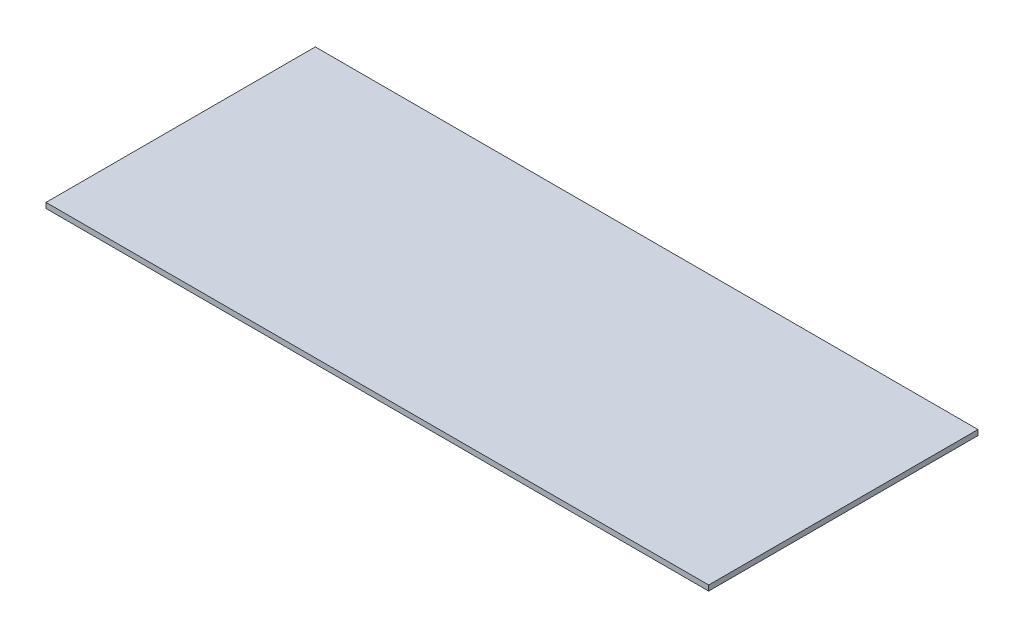
SolidWorks part; units mm, degrees
ref_plane "Front Plane" through (0, 0, 0) normal (0, 0, 1) x (1, 0, 0)
ref_plane "Top Plane" through (0, 0, 0) normal (0, 1, 0) x (1, 0, 0)
ref_plane "Right Plane" through (0, 0, 0) normal (1, 0, 0) x (0, 0, -1)
sketch "Sketch1" plane through (0, 0, 0) normal (0, 1, 0) x (1, 0, 0)
  line L1 (-125, 50.8) -> (125, 50.8)
  line L2 (-125, 50.8) -> (-125, -50.8)
  line L3 (-125, -50.8) -> (125, -50.8)
  line L4 (125, 50.8) -> (125, -50.8)
  line L5 (-125, 50.8) -> (125, -50.8) construction
  line L6 (-125, -50.8) -> (125, 50.8) construction
  point P0 (0, 0)
  dimension "D1" = 250
  dimension "D2" = 101.6
extrude "Boss-Extrude1" add sketch "Sketch1" along normal blind 2
